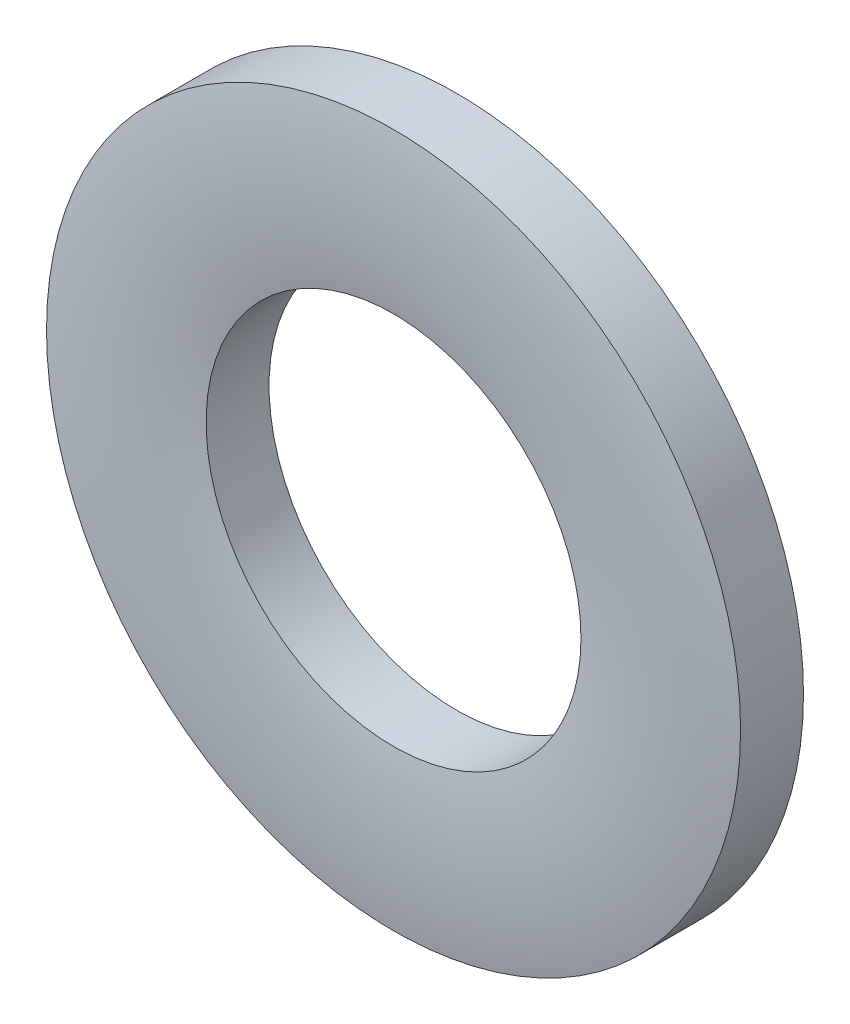
SolidWorks part; units mm, degrees
ref_plane "Front Plane" through (0, 0, 0) normal (0, 0, 1) x (1, 0, 0)
ref_plane "Top Plane" through (0, 0, 0) normal (0, 1, 0) x (1, 0, 0)
ref_plane "Right Plane" through (0, 0, 0) normal (1, 0, 0) x (0, 0, -1)
sketch "Sketch1" plane through (0, 0, 0) normal (0, 0, 1) x (1, 0, 0)
  circle A0 centre (0, 0) radius 1.35
  circle A1 centre (0, 0) radius 2.5
  dimension "ID" = 2.7
  dimension "OD" = 5
sketch "Sketch2" plane through (0, 0, 0) normal (1, 0, 0) x (0, 0, -1)
  line L0 (-0.25, 2.5) -> (0.25, 2.5) construction
  line L1 (-0.25, 0) -> (0.25, 0) construction
  point P2 (0, 2.5)
  dimension "Thickness Range" = 0.5
sketch "Sketch3" plane through (0, 0, 0) normal (1, 0, 0) x (0, 0, -1)
  line L0 (0.25, 2.5) -> (-0.2031, 2.5)
  line L1 (0.25, 1.35) -> (-0.2031, 1.35)
  line L2 (0.25, 1.35) -> (0.25, 2.5)
  line L3 (-0.25, 2.5) -> (-0.25, 1.35) construction
  arc A0 (-0.2031, 1.35) -> (-0.2031, 2.5) centre (3.302, 1.925) cw
  point P9 (0, 1.35)
  dimension "D1" = 0.0469
revolve "Revolve1" add sketch "Sketch3" angle 360 about L1
equation "\"D1@Sketch3\"=\"Thickness Range@Sketch2\"*.0937"
